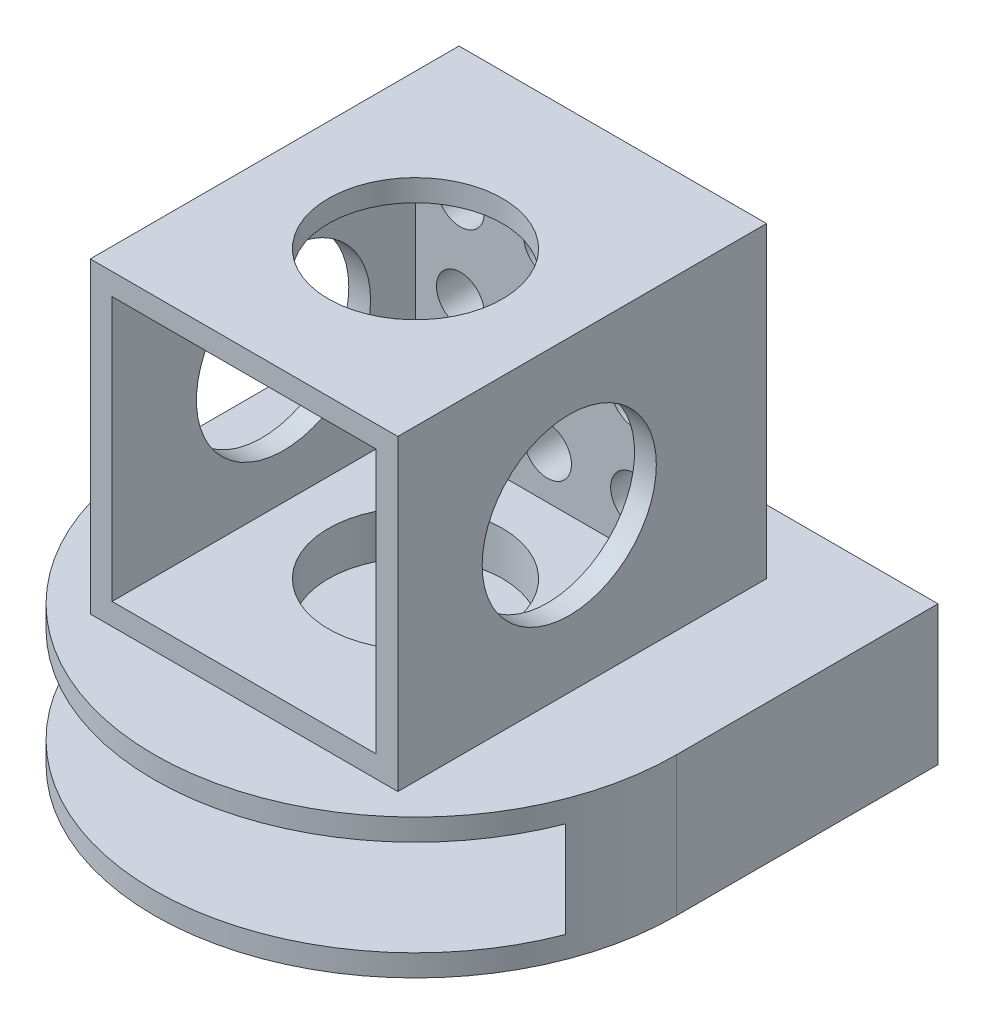
SolidWorks part; units mm, degrees
ref_plane "Front Plane" through (0, 0, 0) normal (0, 0, 1) x (1, 0, 0)
ref_plane "Top Plane" through (0, 0, 0) normal (0, 1, 0) x (1, 0, 0)
ref_plane "Right Plane" through (0, 0, 0) normal (1, 0, 0) x (0, 0, -1)
sketch "Sketch1" plane through (0, 0, 0) normal (0, 1, 0) x (1, 0, 0)
  line L1 (-19.25, -19.25) -> (19.25, -19.25)
  line L2 (-19.25, -19.25) -> (-19.25, 19.25)
  line L3 (-19.25, 19.25) -> (19.25, 19.25)
  line L4 (19.25, -19.25) -> (19.25, 19.25)
  line L5 (-19.25, -19.25) -> (19.25, 19.25) construction
  line L6 (-19.25, 19.25) -> (19.25, -19.25) construction
  line L7 (-22.425, -22.425) -> (22.425, -22.425)
  line L8 (-22.425, -22.425) -> (-22.425, 22.425)
  line L9 (-22.425, 22.425) -> (22.425, 22.425)
  line L10 (22.425, -22.425) -> (22.425, 22.425)
  line L11 (-22.425, -22.425) -> (22.425, 22.425) construction
  line L12 (-22.425, 22.425) -> (22.425, -22.425) construction
  point P0 (0, 0)
  point P6 (0, 0)
  dimension "D1" = 38.5
  dimension "D2" = 38.5
  dimension "D3" = 3.175
  dimension "D4" = 3.175
extrude "Boss-Extrude1" add sketch "Sketch1" along normal mid plane 38.5
sketch "Sketch2" plane through (0, 19.25, 0) normal (0, 1, 0) x (1, 0, 0)
  line L1 (-22.425, 22.425) -> (22.425, 22.425)
  line L2 (-22.425, 22.425) -> (-22.425, -22.425)
  line L3 (-22.425, -22.425) -> (22.425, -22.425)
  line L4 (22.425, 22.425) -> (22.425, -22.425)
extrude "Boss-Extrude2" add sketch "Sketch2" along normal blind 3.175
sketch "Sketch3" plane through (0, -19.25, 0) normal (0, -1, 0) x (1, 0, 0)
  line L1 (22.425, -22.425) -> (-22.425, -22.425)
  line L2 (22.425, -22.425) -> (22.425, 22.425)
  line L3 (22.425, 22.425) -> (-22.425, 22.425)
  line L4 (-22.425, -22.425) -> (-22.425, 22.425)
extrude "Boss-Extrude3" add sketch "Sketch3" along normal blind 3.175
sketch "Sketch5" plane through (0, -22.425, -22.425) normal (0, 1, 0) x (1, 0, 0)
  circle A0 centre (0, -22.425) radius 12.7
  dimension "D1" = 25.4
extrude "Cut-Extrude1" cut sketch "Sketch5" along normal up to next (3.175 mm away) from surface at 0 starting at face at (0, -22.425, 0)
sketch "Sketch8" plane through (0, 0, -22.425) normal (0, 0, -1) x (-1, 0, 0)
  line L0 (-12.7, 12.7) -> (0, 12.7) construction
  line L1 (-22.425, -22.425) -> (22.425, -22.425)
  line L2 (-22.425, 22.425) -> (-22.425, -22.425)
  line L3 (-22.425, 22.425) -> (22.425, 22.425)
  line L4 (22.425, -22.425) -> (22.425, 22.425)
  circle A0 centre (-12.7, 12.7) radius 2.2225
  circle A1 centre (0, 12.7) radius 2.2225
  circle A2 centre (12.7, 12.7) radius 2.2225
  circle A3 centre (0, 0) radius 2.2225
  circle A4 centre (12.7, 0) radius 2.2225
  circle A5 centre (0, -12.7) radius 2.2225
  circle A6 centre (12.7, -12.7) radius 2.2225
  circle A7 centre (-12.7, 0) radius 2.2225
  circle A8 centre (-12.7, -12.7) radius 2.2225
  dimension "D1" = 4.445
  dimension "D2" = 12.7
  dimension "D3" = 12.7
  dimension "D6" = 12.7
  dimension "D4" = 3
  dimension "D5" = 3
extrude "Boss-Extrude4" add sketch "Sketch8" along normal blind 6.35
sketch "Sketch9" plane through (0, 0, -19.25) normal (0, 0, 1) x (1, 0, 0)
  line L0 (12.7, 12.7) -> (0, 12.7) construction
  circle A0 centre (12.7, 12.7) radius 3.4925
  circle A1 centre (0, 12.7) radius 3.4925
  circle A2 centre (-12.7, 12.7) radius 3.4925
  circle A3 centre (0, 0) radius 3.4925
  circle A4 centre (-12.7, 0) radius 3.4925
  circle A5 centre (0, -12.7) radius 3.4925
  circle A6 centre (-12.7, -12.7) radius 3.4925
  circle A7 centre (12.7, 0) radius 3.4925
  circle A8 centre (12.7, -12.7) radius 3.4925
  dimension "D1" = 6.985
  dimension "D4" = 12.7
  dimension "D2" = 3
  dimension "D3" = 3
extrude "Cut-Extrude4" cut sketch "Sketch9" against normal blind 6.35
sketch "Sketch10" plane through (0, 0, 22.425) normal (0, 0, 1) x (1, 0, 0)
  line L0 (-22.425, 22.425) -> (-22.425, -22.425) construction
  line L1 (-19.25, -19.25) -> (19.25, -19.25)
  line L2 (-19.25, -19.25) -> (-19.25, 19.25)
  line L3 (-19.25, 19.25) -> (19.25, 19.25)
  line L4 (19.25, -19.25) -> (19.25, 19.25)
  line L5 (-19.25, -19.25) -> (19.25, 19.25) construction
  line L6 (-19.25, 19.25) -> (19.25, -19.25) construction
  line L7 (-22.425, 22.425) -> (22.425, 22.425) construction
  point P0 (0, 0)
  dimension "D1" = 3.175
  dimension "D2" = 3.175
extrude "Cut-Extrude5" cut sketch "Sketch10" against normal up to next
sketch "Sketch15" plane through (0, 0, 22.425) normal (0, 0, 1) x (1, 0, 0)
  line L1 (-19.25, 19.25) -> (19.25, 19.25)
  line L2 (-19.25, 19.25) -> (-19.25, -19.25)
  line L3 (-19.25, -19.25) -> (19.25, -19.25)
  line L4 (19.25, 19.25) -> (19.25, -19.25)
  line L8 (22.425, 22.425) -> (-22.425, 22.425)
  line L9 (-22.425, 22.425) -> (-22.425, -22.425)
  line L10 (-22.425, -22.425) -> (22.425, -22.425)
  line L11 (-22.425, 22.425) -> (-22.425, -22.425)
  line L12 (22.425, -22.425) -> (22.425, 22.425)
  line L13 (22.425, -22.425) -> (22.425, 22.425)
  line L16 (22.425, 22.425) -> (-22.425, 22.425)
  line L18 (-22.425, -22.425) -> (22.425, -22.425)
  dimension "D1" = 0
extrude "Boss-Extrude8" add sketch "Sketch15" along normal offset from surface (2.575 mm away) 25 up to plane "Front Plane"
sketch "Sketch7" plane through (0, 0, 0) normal (-1, 0, 0) x (0, 0, 1)
  circle A0 centre (0, 0) radius 12.7
  dimension "D1" = 25.4
extrude "Cut-Extrude3" cut sketch "Sketch7" against normal through all both and the other way through all from surface at 0 starting at plane "Right Plane"
sketch "Sketch16" plane through (0, -22.425, 0) normal (0, -1, 0) x (1, 0, 0)
  circle A0 centre (0, 0) radius 34.925
  circle A1 centre (0, 0) radius 38.1
  dimension "D1" = 69.85
  dimension "D2" = 76.2
extrude "Boss-Extrude9" add sketch "Sketch16" along normal blind 20.32 contours A1
sketch "Sketch6" plane through (0, 0, 0) normal (0, 1, 0) x (1, 0, 0)
  circle A0 centre (0, 0) radius 12.7
  dimension "D1" = 25.4
extrude "Cut-Extrude2" cut sketch "Sketch6" against normal through all both and the other way through all
sketch "Sketch17" plane through (0, -42.745, 0) normal (0, -1, 0) x (1, 0, 0)
  line L0 (-35.56, 0) -> (-35.56, 38.1)
  line L1 (-35.56, 38.1) -> (35.56, 38.1)
  line L2 (35.56, 38.1) -> (35.56, 0)
  arc A0 (-35.56, 0) -> (35.56, 0) centre (0, 0) ccw
  circle A1 centre (0, 0) radius 38.1 construction
  point P8 (-34.925, 57.338)
  dimension "D1" = 71.12
extrude "Cut-Extrude6" cut sketch "Sketch17" against normal blind 13.97 from offset 3.175 offset against normal yes
sketch "Sketch18" plane through (0, 0, 0) normal (0, 0, 1) x (1, 0, 0)
  line L1 (38.1, -22.425) -> (-38.1, -22.425)
  line L2 (38.1, -22.425) -> (38.1, -42.745)
  line L3 (38.1, -42.745) -> (-38.1, -42.745)
  line L4 (-38.1, -22.425) -> (-38.1, -42.745)
extrude "Boss-Extrude10" add sketch "Sketch18" along normal up to body from offset 38.1
